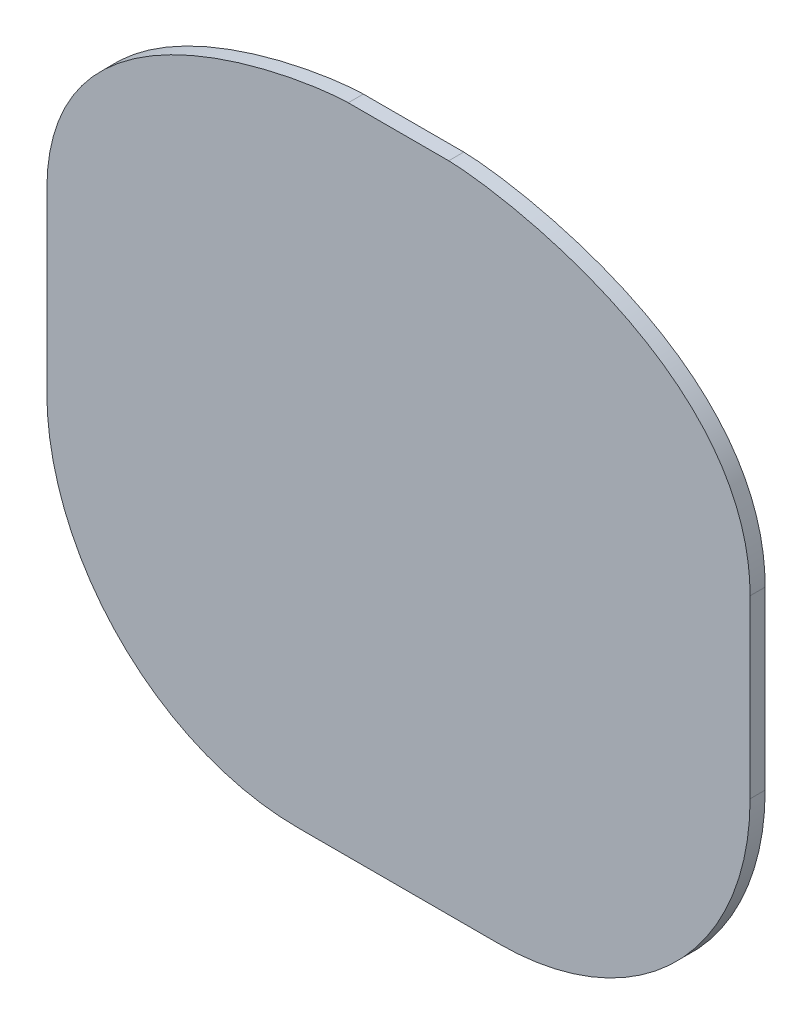
SolidWorks part; units mm, degrees
ref_plane "Front Plane" through (0, 0, 0) normal (0, 0, 1) x (1, 0, 0)
ref_plane "Top Plane" through (0, 0, 0) normal (0, 1, 0) x (1, 0, 0)
ref_plane "Right Plane" through (0, 0, 0) normal (1, 0, 0) x (0, 0, -1)
sketch "Sketch1" plane through (0, 0, 0) normal (0, 0, 1) x (1, 0, 0)
  line L0 (0, 33.5) -> (0, -96.5) construction
  line L1 (-70, 33.5) -> (70, 33.5) construction
  line L2 (-70, 33.5) -> (-70, -96.5) construction
  line L3 (-70, -96.5) -> (70, -96.5) construction
  line L4 (70, 33.5) -> (70, -96.5) construction
  line L5 (-25, 33.5) -> (25, 33.5) construction
  line L6 (-20, -96.5) -> (20, -96.5) construction
  line L7 (-70, -11.5) -> (70, -11.5) construction
  line L8 (-70, -11.5) -> (-70, -46.5)
  line L9 (-70, -46.5) -> (70, -46.5) construction
  line L10 (70, -11.5) -> (70, -46.5)
  line L11 (-10, 33.5) -> (10, 33.5)
  line L12 (20.2739, -96.5) -> (21.2739, -96.5)
  line L13 (-20, -96.5) -> (20.2739, -96.5)
  line L14 (21.2739, -96.5) -> (20, -96.5)
  line L15 (-70, -11.5) -> (-70, 26.5) construction
  line L16 (-70, 26.5) -> (-18, 33.5) construction
  line L17 (-18, 33.5) -> (-10, 33.5) construction
  line L18 (10, 33.5) -> (18, 33.5) construction
  line L19 (18, 33.5) -> (70, 26.5) construction
  line L20 (70, 26.5) -> (70, -11.5) construction
  line L21 (55, 0) -> (-55, 0) construction
  arc A0 (-70, -11.5) -> (-25, 33.5) centre (-25, -11.5) cw construction
  arc A1 (25, 33.5) -> (70, -11.5) centre (25, -11.5) cw construction
  arc A2 (-70, -46.5) -> (-20, -96.5) centre (-20, -46.5) ccw
  arc A3 (20, -96.5) -> (70, -46.5) centre (20, -46.5) ccw
  spline S0 degree 3 poles (-70, -11.5) (-70, 26.5) (-18, 33.5) (-10, 33.5) knots 0 0 0 0 1 1 1 1
  spline S1 degree 3 poles (10, 33.5) (18, 33.5) (70, 26.5) (70, -11.5) knots 0 0 0 0 1 1 1 1
  point P6 (0, -31.5)
  point P10 (0, 33.5)
  point P19 (0, -96.5)
  point P24 (0, 33.5)
  point P30 (0, 0)
  point P32 (-18, 19.1384)
  point P33 (-18, 0)
  point P34 (-70, -7)
  point P35 (-18, -1.5335)
  point P36 (-67.0663, -7)
  point P37 (0, 0)
  point P38 (0, 0)
  point P39 (0, 0)
  point P40 (7.4102, 0)
  dimension "D3" = 50
  dimension "D1" = 130
  dimension "D2" = 140
  dimension "D4" = 20
  dimension "D5" = 45
  dimension "D6" = 38
  dimension "D7" = 52
  dimension "D8" = 52
  dimension "D9" = 38
  dimension "D10" = 33.5
extrude "Boss-Extrude1" add sketch "Sketch1" along normal blind 3 contours S1 L11 S0 L8 A2 L13 A3 L10
